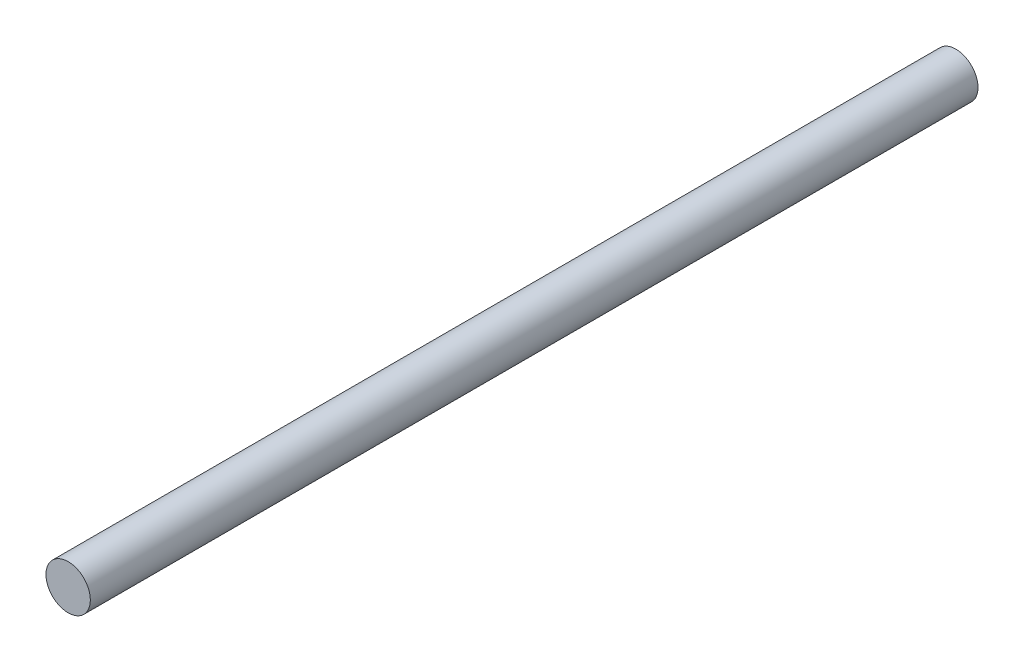
SolidWorks part; units mm, degrees
ref_plane "Front Plane" through (0, 0, 0) normal (0, 0, 1) x (1, 0, 0)
ref_plane "Top Plane" through (0, 0, 0) normal (0, 1, 0) x (1, 0, 0)
ref_plane "Right Plane" through (0, 0, 0) normal (1, 0, 0) x (0, 0, -1)
sketch "Croquis1" plane through (0, 0, 0) normal (0, 0, 1) x (1, 0, 0)
  circle A0 centre (0, 0) radius 2.5
  dimension "D1" = 5
extrude "Saliente-Extruir1" add sketch "Croquis1" along normal blind 100
